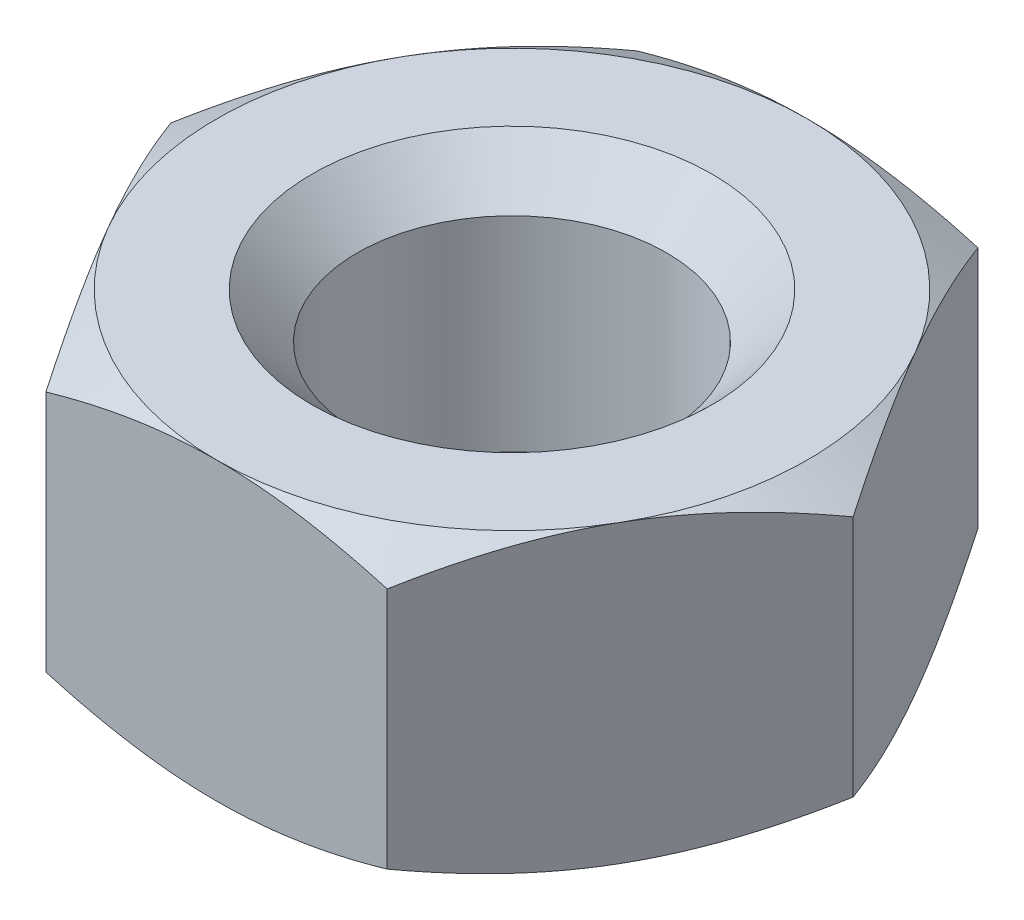
SolidWorks part; units mm, degrees
ref_plane "Front Plane" through (0, 0, 0) normal (0, 0, 1) x (1, 0, 0)
ref_plane "Top Plane" through (0, 0, 0) normal (0, 1, 0) x (1, 0, 0)
ref_plane "Right Plane" through (0, 0, 0) normal (1, 0, 0) x (0, 0, -1)
sketch "Sketch1" plane through (0, 0, 0) normal (0, 1, 0) x (1, 0, 0)
  line L1 (3.7528, 6.5) -> (-3.7528, 6.5)
  line L2 (-3.7528, 6.5) -> (-7.5056, 0)
  line L3 (-7.5056, 0) -> (-3.7528, -6.5)
  line L4 (-3.7528, -6.5) -> (3.7528, -6.5)
  line L5 (3.7528, -6.5) -> (7.5056, 0)
  line L6 (7.5056, 0) -> (3.7528, 6.5)
  circle A0 centre (0, 0) radius 6.5 construction
  dimension "D1" = 13
extrude "Boss-Extrude1" add sketch "Sketch1" along normal blind 6.5
sketch "Sketch2" plane through (0, 0, 0) normal (1, 0, 0) x (0, 0, -1)
  line L0 (-6.5, 6.5) -> (-9.9641, 6.5)
  line L1 (-9.9641, 6.5) -> (-9.9641, 4.5)
  line L2 (-9.9641, 4.5) -> (-6.5, 6.5)
  line L3 (-6.5, 0) -> (-9.9641, 0)
  line L4 (-9.9641, 0) -> (-9.9641, 2)
  line L5 (-9.9641, 2) -> (-6.5, 0)
  line L6 (-6.5, 0) -> (-6.4972, 0.0614)
  line L7 (0, 0) -> (0, 6.5) construction
  dimension "D1" = 30
  dimension "D2" = 2
  dimension "D3" = 30
  dimension "D4" = 2
revolve "Cut-Revolve1" cut sketch "Sketch2" angle 360 about L7
hole_wizard "M8 Tapped Hole1" positions "Sketch5" profile "Sketch4" tap size "M8" standard "DIN" end condition up to next
sketch "Sketch5" plane through (0, 6.5, 0) normal (0, 1, 0) x (-1, 0, 0)
  point P0 (0, 0)
cosmetic thread "Hole Thread1" parameters "D2"=8
sketch "Sketch4" plane through (0, 6.5, 0) normal (1, 0, 0) x (0, 0, 1)
  line L0 (0, 0) -> (0, 6.5)
  line L1 (0, 6.5) -> (3.4, 6.5)
  line L2 (3.4, 6.5) -> (3.4, 0)
  line L5 (3.4, 0) -> (0, 0)
  line L11 (0, -6.35) -> (0, 107.95) construction
  dimension "Thru Tap Drill Dia." = 6.8
  dimension "Thru Tap Drill Depth" = 6.5
chamfer "Chamfer1" distance 1 angle 45 2 edges at (0, 6.5, 3.4) (0, 0, 3.4)
